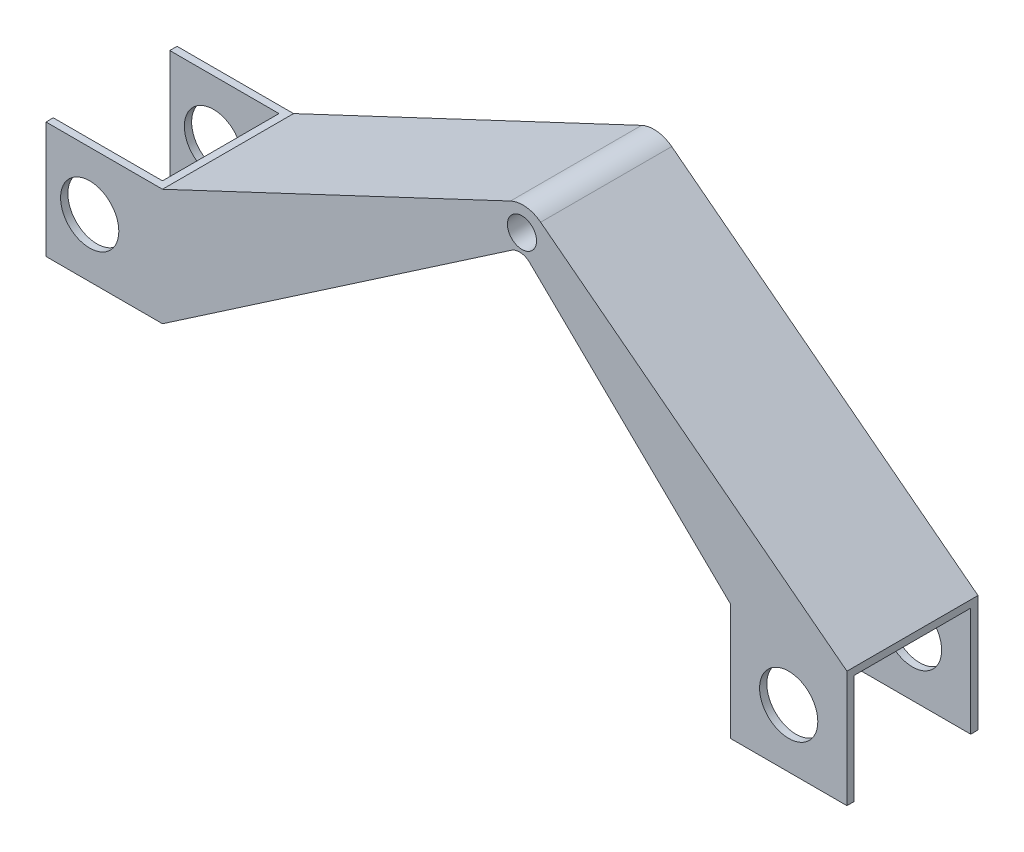
SolidWorks part; units mm, degrees
material "1060 Alloy"
ref_plane "Front Plane" through (0, 0, 0) normal (0, 0, 1) x (1, 0, 0)
ref_plane "Top Plane" through (0, 0, 0) normal (0, 1, 0) x (1, 0, 0)
ref_plane "Right Plane" through (0, 0, 0) normal (1, 0, 0) x (0, 0, -1)
sketch "Sketch1" plane through (0, 0, 0) normal (0, 0, 1) x (1, 0, 0)
  line L1 (-101.6, -101.6) -> (101.6, -101.6)
  line L2 (-101.6, -101.6) -> (-101.6, 101.6)
  line L3 (-101.6, 101.6) -> (101.6, 101.6)
  line L4 (101.6, -101.6) -> (101.6, 101.6)
  line L5 (-101.6, -101.6) -> (101.6, 101.6) construction
  line L6 (-101.6, 101.6) -> (101.6, -101.6) construction
  point P0 (0, 0)
  dimension "D1" = 203.2
  dimension "D2" = 203.2
extrude "Boss-Extrude1" add sketch "Sketch1" along normal blind 228.6
sketch "Sketch2" plane through (0, 101.6, 0) normal (0, 1, 0) x (1, 0, 0)
  line L4 (-88.9, -12.7) -> (-131.9201, -12.7)
  line L5 (-131.9201, -12.7) -> (-131.9201, -215.9)
  line L6 (-131.9201, -215.9) -> (-88.9, -215.9)
  line L8 (88.9, -12.7) -> (-88.9, -12.7)
  line L9 (-88.9, -12.7) -> (-88.9, -215.9)
  line L10 (-88.9, -215.9) -> (88.9, -215.9)
  line L11 (88.9, -215.9) -> (88.9, -12.7)
  line L12 (88.9, -12.7) -> (-88.9, -12.7)
  line L14 (-88.9, -215.9) -> (88.9, -215.9)
  line L15 (88.9, -215.9) -> (88.9, -12.7)
  dimension "D1" = 12.7
extrude "Cut-Extrude1" cut sketch "Sketch2" against normal blind 228.6
sketch "Sketch3" plane through (0, 0, 228.6) normal (0, 0, 1) x (1, 0, 0)
  line L2 (-101.6, 101.6) -> (-101.6, -101.6) construction
  circle A0 centre (-25.4, 0) radius 50.8
  dimension "D1" = 101.6
  dimension "D2" = 76.2
extrude "Cut-Extrude2" cut sketch "Sketch3" against normal through all
sketch "Sketch5" plane through (0, 0, 0) normal (0, 0, 1) x (1, 0, 0)
  line L0 (101.6, 101.6) -> (708.5547, 387.2821)
  line L1 (761.1665, 381.5807) -> (1295.4, -29.4648)
  line L2 (101.6, -101.6) -> (710.1086, 313.6851)
  line L3 (742.1335, 310.9159) -> (1092.2, -29.4648)
  line L4 (101.6, 101.6) -> (101.6, -101.6)
  line L5 (1092.2, -29.4648) -> (1092.2, -232.6648)
  line L6 (1092.2, -232.6648) -> (1295.4, -232.6648)
  line L7 (1295.4, -232.6648) -> (1295.4, -29.4648)
  arc A0 (708.5547, 387.2821) -> (761.1665, 381.5807) centre (730.1886, 341.3189) cw
  arc A1 (710.1086, 313.6851) -> (742.1335, 310.9159) centre (724.4266, 292.7052) cw
  point P12 (736.6, 400.4825)
  dimension "D5" = 50.8
  dimension "D6" = 25.4
  dimension "D1" = 635
  dimension "D2" = 558.8
  dimension "D3" = 203.2
  dimension "D4" = 203.2
extrude "Boss-Extrude2" add sketch "Sketch5" along normal blind 228.6
sketch "Sketch6" plane through (1092.2, 0, 0) normal (-1, 0, 0) x (0, 0, 1)
  line L4 (12.7, -219.9648) -> (12.7, -266.7294)
  line L5 (12.7, -266.7294) -> (215.9, -266.7294)
  line L6 (215.9, -266.7294) -> (215.9, -219.9648)
  line L8 (12.7, -42.1648) -> (12.7, -219.9648)
  line L9 (12.7, -219.9648) -> (215.9, -219.9648)
  line L10 (215.9, -219.9648) -> (215.9, -42.1648)
  line L11 (215.9, -42.1648) -> (12.7, -42.1648)
  line L12 (12.7, -42.1648) -> (12.7, -219.9648)
  line L14 (215.9, -219.9648) -> (215.9, -42.1648)
  line L15 (215.9, -42.1648) -> (12.7, -42.1648)
  dimension "D1" = 12.7
extrude "Cut-Extrude3" cut sketch "Sketch6" against normal through all
sketch "Sketch7" plane through (0, 0, 228.6) normal (0, 0, 1) x (1, 0, 0)
  line L0 (1295.4, -232.6648) -> (1295.4, -29.4648) construction
  circle A0 centre (1193.8, -131.0648) radius 50.8
  dimension "D1" = 101.6
  dimension "D2" = 101.6
  dimension "D3" = 101.6
extrude "Cut-Extrude4" cut sketch "Sketch7" against normal through all
sketch "Sketch8" plane through (0, 0, 228.6) normal (0, 0, 1) x (1, 0, 0)
  circle A0 centre (728.6156, 349.5692) radius 25.4
  dimension "D1" = 50.8
extrude "Cut-Extrude5" cut sketch "Sketch8" against normal through all
